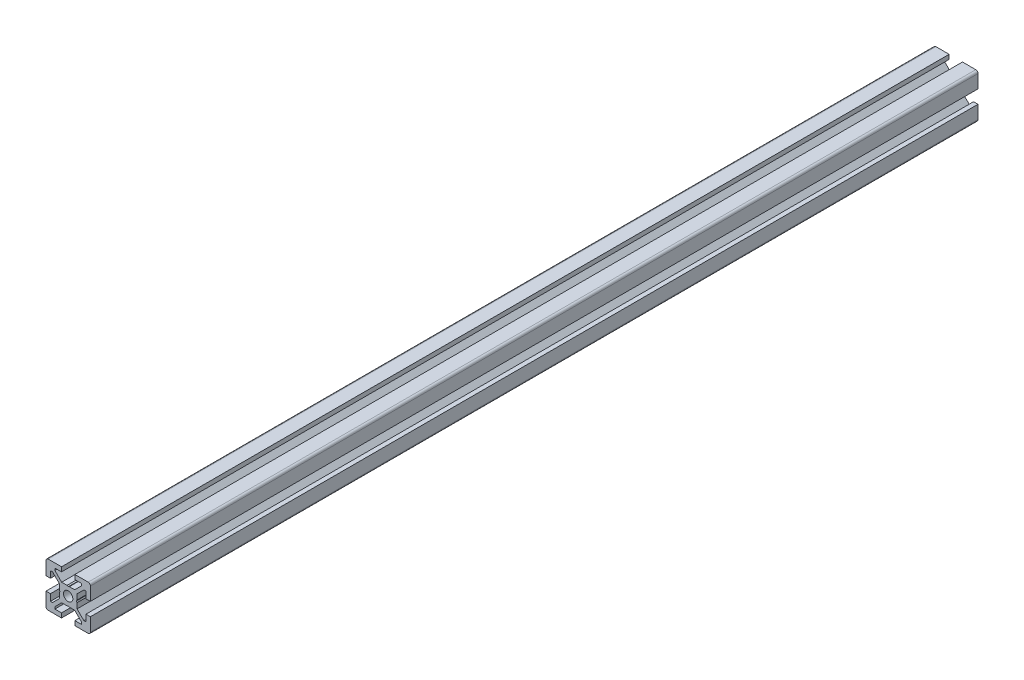
SolidWorks part; units mm, degrees
ref_plane "Front Plane" through (0, 0, 0) normal (0, 0, 1) x (1, 0, 0)
ref_plane "Top Plane" through (0, 0, 0) normal (0, 1, 0) x (1, 0, 0)
ref_plane "Right Plane" through (0, 0, 0) normal (1, 0, 0) x (0, 0, -1)
ref_plane "Plane1" through (0, 0, 0) normal (0, 0, 1) x (1, 0, 0)
sketch "Sketch1" plane through (0, 0, 0) normal (0, 0, 1) x (1, 0, 0)
  line L0 (-10, -3) -> (-10, -9)
  line L1 (-9, -10) -> (-3, -10)
  line L2 (-3, -10) -> (-3, -8)
  line L3 (-3, -8) -> (-6, -8)
  line L4 (-6, -8) -> (-6, -7.0607)
  line L5 (-6, -7.0607) -> (-2.9393, -4)
  line L6 (-2.9393, -4) -> (-0.5196, -4)
  line L7 (-0.5196, -4) -> (0, -3.7)
  line L8 (0, -3.7) -> (0.5196, -4)
  line L9 (0.5196, -4) -> (2.9393, -4)
  line L10 (2.9393, -4) -> (6, -7.0607)
  line L11 (6, -7.0607) -> (6, -8)
  line L12 (6, -8) -> (3, -8)
  line L13 (3, -8) -> (3, -10)
  line L14 (3, -10) -> (9, -10)
  line L15 (10, -9) -> (10, -3)
  line L16 (10, -3) -> (8, -3)
  line L17 (8, -3) -> (8, -6)
  line L18 (8, -6) -> (7.0607, -6)
  line L19 (7.0607, -6) -> (4, -2.9393)
  line L20 (4, -2.9393) -> (4, -0.5196)
  line L21 (4, -0.5196) -> (3.7, 0)
  line L22 (3.7, 0) -> (4, 0.5196)
  line L23 (4, 0.5196) -> (4, 2.9393)
  line L24 (4, 2.9393) -> (7.0607, 6)
  line L25 (7.0607, 6) -> (8, 6)
  line L26 (8, 6) -> (8, 3)
  line L27 (8, 3) -> (10, 3)
  line L28 (10, 3) -> (10, 9)
  line L29 (9, 10) -> (3, 10)
  line L30 (3, 10) -> (3, 8)
  line L31 (3, 8) -> (6, 8)
  line L32 (6, 8) -> (6, 7.0607)
  line L33 (6, 7.0607) -> (2.9393, 4)
  line L34 (2.9393, 4) -> (0.5196, 4)
  line L35 (0.5196, 4) -> (0, 3.7)
  line L36 (0, 3.7) -> (-0.5196, 4)
  line L37 (-0.5196, 4) -> (-2.9393, 4)
  line L38 (-2.9393, 4) -> (-6, 7.0607)
  line L39 (-6, 7.0607) -> (-6, 8)
  line L40 (-6, 8) -> (-3, 8)
  line L41 (-3, 8) -> (-3, 10)
  line L42 (-3, 10) -> (-9, 10)
  line L43 (-10, 9) -> (-10, 3)
  line L44 (-10, 3) -> (-8, 3)
  line L45 (-8, 3) -> (-8, 6)
  line L46 (-8, 6) -> (-7.0607, 6)
  line L47 (-7.0607, 6) -> (-4, 2.9393)
  line L48 (-4, 2.9393) -> (-4, 0.5196)
  line L49 (-4, 0.5196) -> (-3.7, 0)
  line L50 (-3.7, 0) -> (-4, -0.5196)
  line L51 (-4, -0.5196) -> (-4, -2.9393)
  line L52 (-4, -2.9393) -> (-7.0607, -6)
  line L53 (-7.0607, -6) -> (-8, -6)
  line L54 (-8, -6) -> (-8, -3)
  line L55 (-8, -3) -> (-10, -3)
  arc A0 (-10, -9) -> (-9, -10) centre (-9, -9) ccw
  arc A1 (9, -10) -> (10, -9) centre (9, -9) ccw
  arc A2 (10, 9) -> (9, 10) centre (9, 9) ccw
  arc A3 (-9, 10) -> (-10, 9) centre (-9, 9) ccw
extrude "Boss-Extrude1" add sketch "Sketch1" against normal blind 400
ref_plane "Plane2" through (0, 0, 0) normal (1, 0, 0) x (0, 0, -1)
sketch "Sketch2" plane through (0, 0, 0) normal (1, 0, 0) x (0, 0, -1)
  line L0 (0, 0) -> (0, 2.1)
  line L1 (0, 2.1) -> (400, 2.1)
  line L2 (400, 2.1) -> (400, 0)
  line L3 (400, 0) -> (0, 0)
  line L4 (400, 0) -> (0, 0) construction
revolve "Cut-Revolve1" cut sketch "Sketch2" angle 360 about L4
